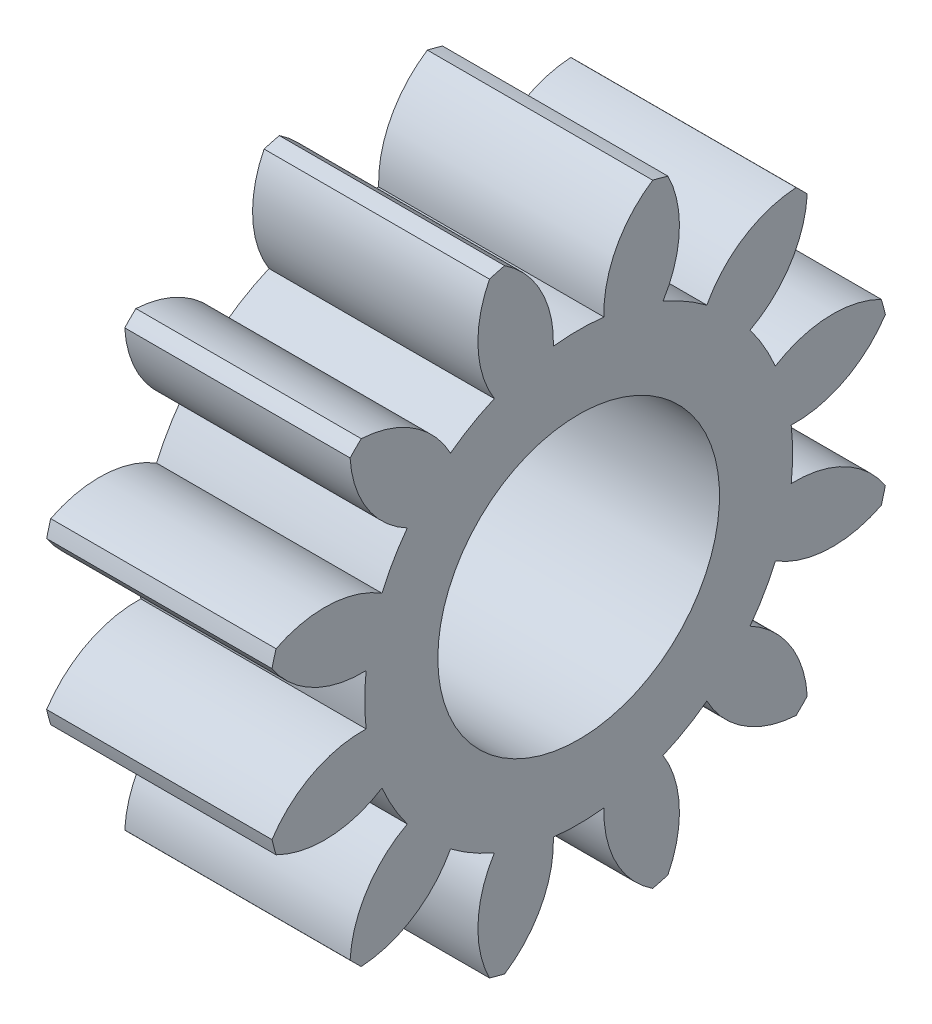
SolidWorks part; units mm, degrees
ref_plane "Plane1" through (0, 0, 0) normal (0, 0, 1) x (1, 0, 0)
ref_plane "Plane2" through (0, 0, 0) normal (0, 1, 0) x (1, 0, 0)
ref_plane "Plane3" through (0, 0, 0) normal (1, 0, 0) x (0, 0, -1)
sketch "HoldingSke" plane through (0, 0, 0) normal (0, 1, 0) x (1, 0, 0)
  line L0 (0, 0) -> (1.2227, -0.2599)
  line L1 (-15, 0) -> (100, 0) construction
  line L2 (0, 0) -> (-2.1039, 2.3779)
  line L3 (0, 0) -> (-11.863, 4.5341)
  line L4 (0, 0) -> (8.4473, 1.7955)
  line L5 (0, 0) -> (-46.8476, -17.4728)
  line L6 (0, 0) -> (-3.3159, -2.2372)
  line L7 (-2.1039, 2.3779) -> (8.6586, 51.2059)
  line L8 (-76.2, 54.61) -> (-75.3, 54.61)
  line L9 (-71.009, 38.7566) -> (-53.1078, 45.2721)
  line L10 (-76.2, 71.12) -> (104.1128, 71.12)
  line L11 (0, 0) -> (-4, 0)
  line L12 (-76.2, 101.6) -> (-76.17, 101.6)
  line L13 (24.9733, 27.94) -> (52.9518, 28.4284)
  line L14 (24.9733, 27.94) -> (24.9743, 27.94)
  line L15 (24.9733, 27.94) -> (100.4006, 29.5858)
  line L16 (-63.627, -0.8) -> (-12.827, -0.8)
  circle A0 centre (0, 0) radius 2.5
  circle A1 centre (0, 0) radius 3.799
  circle A2 centre (0, 0) radius 37.5
  circle A3 centre (0, 0) radius 2.5
  dimension "MHD" = 7.598
  dimension "Hub_dia" = 75
  dimension "Bore" = 5
  dimension "MBD" = 5
  dimension "Num_teeth" = 12
  dimension "Pitch" = 1.25
  dimension "Overall_len" = 50
  dimension "Show_teeth" = 12
  dimension "Thickness" = 4
  dimension "OAL" = 50.0001
  dimension "T_dim" = 0.9
  dimension "Ap" = 20
  dimension "H" = 19.05
  dimension "Pitch_radius" = 180.3128
  dimension "Width" = 4
  dimension "Backlash" = 0.03
  dimension "Addendum_fac" = 1
  dimension "Dedendum_fac" = 1.25
  dimension "Clearance_fac" = 0.25
  dimension "Dedendum_add" = 0.001
  dimension "Module" = 0.8
sketch "BasProSke" plane through (0, 0, 0) normal (0, 1, 0) x (1, 0, 0)
  line L0 (-10, 0) -> (60, 0) construction
  line L1 (0, 0) -> (0, 5.6)
  line L2 (0, 0) -> (4, 0)
  line L3 (4, 0) -> (4, 5.6)
  line L4 (4, 5.6) -> (0, 5.6)
  dimension "Thickness" = 4
  dimension "Diameter" = 11.2
revolve "Base-Revolve" add sketch "BasProSke" angle 360 about L0
sketch "TooCutSke" plane through (0, 0, 0) normal (1, 0, 0) x (0, 0, -1)
  line L1 (0, 0) -> (0, 107) construction
  line L2 (0, 0) -> (-0.6789, 4.7517) construction
  line L3 (0, 0) -> (-2.4668, 9.2063) construction
  line L4 (-0.6789, 4.7517) -> (-1.2334, 4.6032) construction
  arc A0 (0.4492, 3.7723) -> (-0.4492, 3.7723) centre (0, 0) ccw
  arc A1 (1.3434, 5.4626) -> (-1.3434, 5.4626) centre (0, 0) ccw
  circle A2 centre (0, 0) radius 4.8 construction
  circle A3 centre (0, 0) radius 4.5105 construction
  arc A4 (-0.4492, 3.7723) -> (-1.3434, 5.4626) centre (-2.3681, 3.8389) ccw
  arc A5 (1.3434, 5.4626) -> (0.4492, 3.7723) centre (2.3681, 3.8389) ccw
  dimension "Root_dia" = 7.598
  dimension "Overcut_dia" = 11.2508
  dimension "Pitch_dia" = 9.6
  dimension "Base_dia" = 9.021
  dimension "Flank_rad" = 1.92
  dimension "Half_ang" = 15
  dimension "Half_CT" = 0.574
extrude "ToothCut" cut sketch "TooCutSke" along normal through all
fillet "Breaks" [suppressed] radius 0.016
fillet "RootFillets" [suppressed] radius 0.201
pattern_circular "TeethCuts" count 12 every 30 about axis through (-10, 0, 0) along (1, 0, 0) of "ToothCut", "RootFillets", "Breaks"
sketch "HubNeaOneSke" plane through (0, 0, 0) normal (-1, 0, 0) x (0, 0, 1)
  circle A0 centre (0, 0) radius 3.799
  dimension "Diameter" = 7.598
extrude "HubNearOne" [suppressed] add sketch "HubNeaOneSke" along normal blind 46.0001
sketch "HubNeaBotSke" plane through (0, 0, 0) normal (-1, 0, 0) x (0, 0, 1)
  circle A0 centre (0, 0) radius 3.799
  dimension "Diameter" = 7.598
extrude "HubNearBoth" [suppressed] add sketch "HubNeaBotSke" along normal blind 23
ref_plane "FarPln" through (4, 0, 0) normal (1, 0, 0) x (0, 0, -1)
sketch "HubFarSke" plane through (4, 0, 0) normal (1, 0, 0) x (0, 0, -1)
  circle A0 centre (0, 0) radius 3.799
  dimension "Diameter" = 7.598
extrude "HubFar" [suppressed] add sketch "HubFarSke" along normal blind 23
sketch "BorSke" plane through (0, 0, 0) normal (1, 0, 0) x (0, 0, -1)
  circle A0 centre (0, 0) radius 2.5
  dimension "Diameter" = 5
extrude "Bore" cut sketch "BorSke" along normal mid plane 100.0001
sketch "KeySke" plane through (0, 0, 0) normal (1, 0, 0) x (0, 0, -1)
  line L0 (-1, 0) -> (-1, 3.4)
  line L1 (-1, 3.4) -> (1, 3.4)
  line L2 (1, 3.4) -> (1, 0)
  line L3 (0, 0) -> (0, 34) construction
  line L4 (-1, 0) -> (1, 0)
  dimension "Offset" = 3.4
  dimension "Width" = 2
extrude "Keyway" [suppressed] cut sketch "KeySke" along normal mid plane 100.0001
pattern_circular "Keyway2" [suppressed] count 2 every 90 about axis through (-10, 0, 0) along (1, 0, 0)
equation "' \"Module@HoldingSke\" = 6.35"
equation "' \"Num_teeth@HoldingSke\" = 12"
equation "' \"Ap@HoldingSke\" =  20"
equation "' \"Ap@HoldingSke\" = 20"
equation "' \"Width@HoldingSke\" = 0.5 * 25.4"
equation "' \"Hub_dia@HoldingSke\"= 1 * 25.4"
equation "' \"Hub_dia@HoldingSke\" = 1 * 25.4"
equation "' \"Overall_len@HoldingSke\" = 1.0 * 25.4"
equation "' \"Bore@HoldingSke\" = 0.75 * 25.4"
equation "' \"T_dim@HoldingSke\" = 0.1 * 25.4"
equation "' \"Width@KeySke\" = 0.25 * 25.4"
equation "' \"Show_teeth@HoldingSke\" = 13"
equation "' \"Backlash@HoldingSke\" = 0.009 * 25.4"
equation "' \"Addendum_fac@HoldingSke\" = 1.0"
equation "' \"Dedendum_fac@HoldingSke\" = 1.25"
equation "' \"Dedendum_add@HoldingSke\" = 0.00005 * 25.4"
equation "' \"Clearance_fac@HoldingSke\" = 0.25"
equation "\"Pitch@HoldingSke\" = 1 / \"Module@HoldingSke\""
equation "\"Overcut_dia@TooCutSke\" = (\"Num_teeth@HoldingSke\" + 2 * \"Addendum_fac@HoldingSke\") / \"Pitch@HoldingSke\" + 0.002 * 25.4"
equation "\"Pitch_dia@TooCutSke\" = \"Num_teeth@HoldingSke\" / \"Pitch@HoldingSke\""
equation "\"Base_dia@TooCutSke\" = \"Num_teeth@HoldingSke\" / \"Pitch@HoldingSke\" * cos((\"Ap@HoldingSke\"  * 3.14159265 / 180))"
equation "\"Root_dia@TooCutSke\" = (\"Num_teeth@HoldingSke\" + 2) / \"Pitch@HoldingSke\" - 2 * (\"Addendum_fac@HoldingSke\" + \"Dedendum_fac@HoldingSke\") / \"Pitch@HoldingSke\" - \"Dedendum_add@HoldingSke\" * 2"
equation "\"Half_ang@TooCutSke\" = 180 / \"Num_teeth@HoldingSke\""
equation "\"Half_CT@TooCutSke\" = \"Num_teeth@HoldingSke\" / \"Pitch@HoldingSke\" * sin((3.14159265 / 2 / \"Num_teeth@HoldingSke\")) / 2 - 7 * \"Backlash@HoldingSke\" / 4"
equation "\"Flank_rad@TooCutSke\" = \"Num_teeth@HoldingSke\" / \"Pitch@HoldingSke\" / 5"
equation "\"Radius@RootFillets\" = \"Clearance_fac@HoldingSke\" / \"Pitch@HoldingSke\" + \"Dedendum_add@HoldingSke\""
equation "\"Break_rad@Breaks\" = 0.02 / \"Pitch@HoldingSke\""
equation "\"Thickness@HoldingSke\" = \"Width@HoldingSke\""
equation "\"OAL@HoldingSke\" = \"Thickness@HoldingSke\""
equation "\"MHD@HoldingSke\" = (\"Num_teeth@HoldingSke\" + 2) / \"Pitch@HoldingSke\" - 2 * (\"Addendum_fac@HoldingSke\" + \"Dedendum_fac@HoldingSke\")  / \"Pitch@HoldingSke\" - \"Dedendum_add@HoldingSke\" * 2"
equation "\"MBD@HoldingSke\" = (\"Num_teeth@HoldingSke\" + 2) / \"Pitch@HoldingSke\" - 2 * (\"Addendum_fac@HoldingSke\" + \"Dedendum_fac@HoldingSke\")  / \"Pitch@HoldingSke\" - \"Dedendum_add@HoldingSke\" * 2 - 0.002 * 25.4"
equation "\"MHD@HoldingSke\" = ((sgn( \"MHD@HoldingSke\" - \"Hub_dia@HoldingSke\" )-1)*( \"MHD@HoldingSke\" - \"Hub_dia@HoldingSke\" ))/-2+ \"Hub_dia@HoldingSke\""
equation "\"MBD@HoldingSke\" = ((sgn( \"MBD@HoldingSke\" - \"Bore@HoldingSke\" )-1)*( \"MBD@HoldingSke\" - \"Bore@HoldingSke\" ))/-2+ \"Bore@HoldingSke\""
equation "\"OAL@HoldingSke\" = ((sgn( \"OAL@HoldingSke\" - \"Overall_len@HoldingSke\" )+1)*( \"OAL@HoldingSke\" - \"Overall_len@HoldingSke\" ))/2 + \"Overall_len@HoldingSke\" + 0.000002 * 25.4"
equation "\"Num_teeth@TeethCuts\" = int( \"Show_teeth@HoldingSke\" ) + 1"
equation "\"Num_teeth@TeethCuts\" = ((sgn( \"Num_teeth@TeethCuts\" - \"Num_teeth@HoldingSke\" )-1)*( \"Num_teeth@TeethCuts\" - \"Num_teeth@HoldingSke\" ))/-2+ \"Num_teeth@HoldingSke\""
equation "\"Num_teeth@TeethCuts\" = ((sgn( \"Num_teeth@TeethCuts\" - 2.0)+1)*( \"Num_teeth@TeethCuts\" - 2.0))/2 +2.0"
equation "\"Angle@TeethCuts\" = 360.0 / \"Num_teeth@HoldingSke\""
equation "\"Diameter@BasProSke\" = (\"Num_teeth@HoldingSke\" + 2 * \"Addendum_fac@HoldingSke\") / \"Pitch@HoldingSke\""
equation "\"Thickness@BasProSke\"  = \"Thickness@HoldingSke\""
equation "' \"Fillet_rad@BasProSke\" =  \"Thickness@HoldingSke\" * 0.05"
equation "' \"Fillet_rad@BasProSke\" = \"Thickness@HoldingSke\" * 0.05"
equation "\"MHD@HoldingSke\" = ((sgn( \"MHD@HoldingSke\" - \"Root_dia@TooCutSke\" )-1)*( \"MHD@HoldingSke\" - \"Root_dia@TooCutSke\" ))/-2+ \"Root_dia@TooCutSke\""
equation "\"Diameter@HubNeaOneSke\" = \"MHD@HoldingSke\""
equation "\"Length@HubNearOne\" = \"OAL@HoldingSke\" - \"Thickness@BasProSke\""
equation "\"Diameter@HubNeaBotSke\" = \"MHD@HoldingSke\""
equation "\"Length@HubNearBoth\" = ( \"OAL@HoldingSke\" - \"Thickness@BasProSke\" ) / 2.0"
equation "\"Thickness@FarPln\" = \"Thickness@BasProSke\""
equation "\"Diameter@HubFarSke\" = \"MHD@HoldingSke\""
equation "\"Length@HubFar\" = ( \"OAL@HoldingSke\" - \"Thickness@BasProSke\" ) / 2.0"
equation "\"Diameter@BorSke\" = \"MBD@HoldingSke\""
equation "\"D1@Bore\" = \"OAL@HoldingSke\" * 2.0"
equation "\"D1@Keyway\" = \"OAL@HoldingSke\" * 2.0"
equation "\"Offset@KeySke\" = \"T_dim@HoldingSke\" + \"MBD@HoldingSke\" / 2.0"
